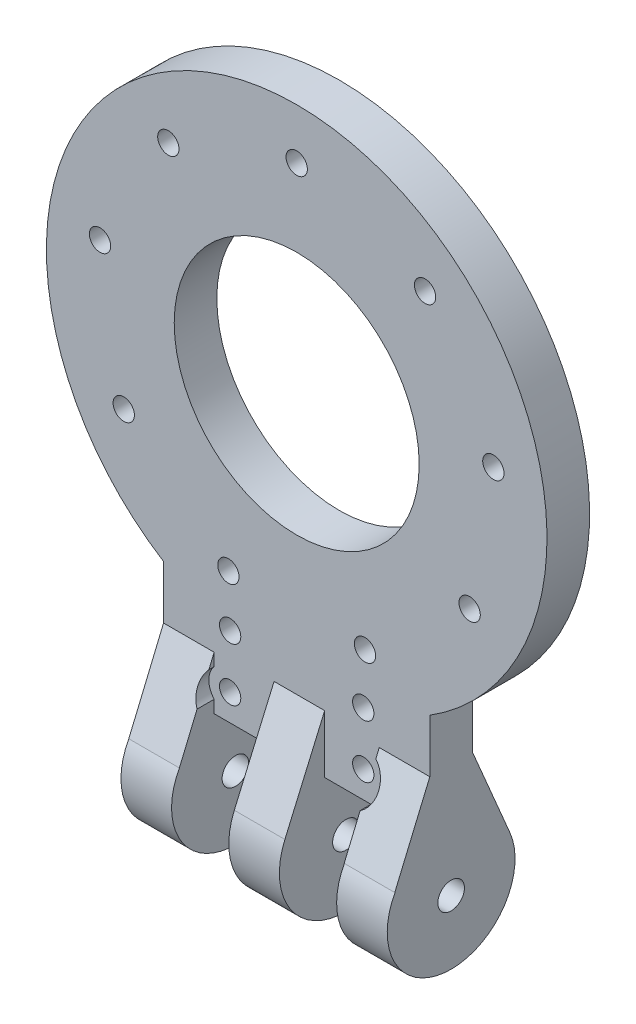
SolidWorks part; units mm, degrees
ref_plane "前视基准面" through (0, 0, 0) normal (0, 0, 1) x (1, 0, 0)
ref_plane "上视基准面" through (0, 0, 0) normal (0, 1, 0) x (1, 0, 0)
ref_plane "右视基准面" through (0, 0, 0) normal (1, 0, 0) x (0, 0, -1)
sketch "草图1" plane through (0, 0, 0) normal (0, 0, 1) x (1, 0, 0)
  line L0 (32.476, 31.0495) -> (36.9303, 56.3113) construction
  line L1 (-25, -10) -> (25, -10)
  line L2 (-25, -10) -> (-25, 10)
  line L3 (-25, 10) -> (25, 10) construction
  line L4 (25, -10) -> (25, 10)
  line L5 (-25, -10) -> (25, 10) construction
  line L6 (-25, 10) -> (25, -10) construction
  line L7 (0, 87.2995) -> (-24.1045, 78.5262) construction
  line L8 (-24.1045, 78.5262) -> (-36.9303, 56.3113) construction
  line L9 (-36.9303, 56.3113) -> (-32.476, 31.0495) construction
  line L10 (-32.476, 31.0495) -> (-12.8258, 14.561) construction
  line L11 (-12.8258, 14.561) -> (12.8258, 14.561) construction
  line L12 (12.8258, 14.561) -> (32.476, 31.0495) construction
  line L13 (36.9303, 56.3113) -> (24.1045, 78.5262) construction
  line L14 (24.1045, 78.5262) -> (0, 87.2995) construction
  line L15 (0, 10) -> (0, -10) construction
  arc A0 (25, 10) -> (-25, 10) centre (0, 49.7995) ccw
  circle A1 centre (0, 49.7995) radius 37.5 construction
  circle A3 centre (24.1045, 78.5262) radius 2
  circle A4 centre (36.9303, 56.3113) radius 2
  circle A5 centre (32.476, 31.0495) radius 2
  circle A6 centre (12.8258, 14.561) radius 2
  circle A7 centre (-12.8258, 14.561) radius 2
  circle A8 centre (-32.476, 31.0495) radius 2
  circle A9 centre (-36.9303, 56.3113) radius 2
  circle A10 centre (-24.1045, 78.5262) radius 2
  circle A11 centre (0, 87.2995) radius 2
  circle A12 centre (12.5, -5) radius 2
  circle A13 centre (-12.5, -5) radius 2
  circle A14 centre (12.5, 5) radius 2
  circle A15 centre (-12.5, 5) radius 2
  circle A16 centre (0, 49.7995) radius 23
  point P0 (0, 0)
  point P36 (0, 49.7995)
  dimension "D3" = 47
  dimension "D4" = 9
  dimension "D5" = 4
  dimension "D6" = 75
  dimension "D7" = 25.2618
  dimension "D8" = 4
  dimension "D11" = 5
  dimension "D12" = 10
  dimension "D13" = 46
  dimension "D1" = 50
  dimension "D2" = 20
  dimension "D9" = 12.5
  dimension "D10" = 2
extrude "凸台-拉伸1" add sketch "草图1" along normal blind 8
sketch "草图2" plane through (-25, 0, 0) normal (-1, 0, 0) x (0, 0, 1)
  arc A0 (0, -10) -> (8, -10) centre (4, -21.3137) ccw
  circle A1 centre (4, -21.3137) radius 2.5
  line M2 (0, -10) -> (8, -10)
  dimension "D1" = 12
  dimension "D2" = 5
extrude "凸台-拉伸2" add sketch "草图2" against normal blind 9.5 contours A0 A1 M2
sketch "草图4" plane through (25, 0, 0) normal (1, 0, 0) x (0, 0, -1)
  line L4 (0, -10) -> (0, 10)
  line L5 (0, 10) -> (-8, 10)
  line L6 (-8, 10) -> (-8, -10)
  line L7 (-8, -10) -> (0, -10)
  line L11 (-8, -10) -> (0, -10)
  arc A0 (-8, -10) -> (0, -10) centre (-4, -21.3137) ccw
  circle A1 centre (-4, -21.3137) radius 2.5
  dimension "D1" = 0
extrude "凸台-拉伸4" add sketch "草图4" against normal blind 9.5
sketch "草图5" plane through (0, -10, 0) normal (0, -1, 0) x (1, 0, 0)
  line L0 (-15.5, 8) -> (15.5, 8) construction
  line L1 (0, 8) -> (0, 0) construction
ref_plane "基准面5" through (0.5, 0, 0) normal (-1, 0, 0) x (0, 0, 1)
sketch "草图6" plane through (0.5, 0, 0) normal (-1, 0, 0) x (0, 0, 1)
  arc A0 (0, -10) -> (8, -10) centre (4, -21.3137) ccw
  circle A1 centre (4, -21.3137) radius 2.5
  dimension "D1" = 12
  dimension "D2" = 5
extrude "拉伸-薄壁1" add sketch "草图6" along normal mid plane 9.5 thin contours A1
sketch "草图7" plane through (-25, 0, 0) normal (-1, 0, 0) x (0, 0, 1)
  line L0 (8, 0) -> (15.4824, -17.8274)
  line L1 (8, 10) -> (8, -10) construction
  arc A0 (0, -10) -> (8, -10) centre (4, -21.3137) ccw construction
rib "筋1" sketch "草图7" sketch "草图7" thickness 9.5 extrusion direction parallel to sketch draft on no parameters "D1"=9.5
sketch "草图10" plane through (-25, 0, 0) normal (-1, 0, 0) x (0, 0, 1)
  line L0 (0, 0) -> (-7.0486, -16.631) construction
  line L1 (0, 10) -> (0, -10) construction
  line L2 (8, 0) -> (0, 0) construction
  arc A0 (0, -10) -> (8, -10) centre (4, -21.3137) ccw construction
sketch "草图12" plane through (25, 0, 0) normal (1, 0, 0) x (0, 0, -1)
  line L0 (-8, 0) -> (-14.5853, -15.5378)
  line L2 (-8, 0) -> (-3.3764, -1.9426)
  line L3 (-3.3764, -1.9426) -> (-9.6471, -16.8675)
  line L4 (-9.6471, -16.8675) -> (-14.5853, -15.5378)
  arc A1 (-8, -10) -> (0, -10) centre (-4, -21.3137) ccw construction
extrude "凸台-拉伸5" add sketch "草图12" against normal up to surface (9.5 mm away) up to face at (15.5, -21.3137, 1.5)
sketch "草图14" plane through (25, 0, 0) normal (1, 0, 0) x (0, 0, -1)
  line L0 (0, 0) -> (7.0486, -16.631)
  line L1 (0, -10) -> (0, 10) construction
  arc A0 (-14.5271, -15.5534) -> (0, -10) centre (-4, -21.3137) ccw construction
sketch "草图15" plane through (-25, 0, 0) normal (-1, 0, 0) x (0, 0, 1)
  line L1 (0, 0) -> (-7.0486, -16.631)
  line L2 (-7.0486, -16.631) -> (-1.0813, -18.152)
  line L3 (-1.0813, -18.152) -> (5.6051, -2.3756)
  line L4 (5.6051, -2.3756) -> (0, 0)
  arc A0 (0, -10) -> (8, -10) centre (4, -21.3137) ccw construction
extrude "凸台-拉伸6" add sketch "草图15" against normal up to surface (9.5 mm away) up to face at (-15.5, -21.3137, 6.5)
sketch "草图20" plane through (0, 0, 8) normal (0, 0, 1) x (1, 0, 0)
  line L0 (0.5, 30.6594) -> (0.5, -30.6594) construction
  circle A0 centre (-12.5, -5) radius 4
  circle A1 centre (13.5, -5) radius 4
extrude "切除-拉伸3" cut sketch "草图20" along normal up to surface (2.1191 mm away)
sketch "草图23" plane through (0.5, 0, 0) normal (-1, 0, 0) x (0, 0, 1)
  line L0 (0, 0) -> (-7.3682, -16.1162)
  line L1 (-7.3682, -16.1162) -> (-3.8416, -16.9118)
  line L2 (-3.8416, -16.9118) -> (3.2466, -1.408)
  line L3 (3.2466, -1.408) -> (-0.1261, -0.2759)
  arc A0 (0, -9.471) -> (8, -9.471) centre (4, -21.3137) ccw construction
extrude "凸台-拉伸7" add sketch "草图23" along normal up to surface and the other way up to surface contours L2 L3 L0 L1 up to face at (-4.25, -15.8212, 4) other way up to face at (5.25, -15.8212, 4)
sketch "草图25" plane through (0, 0, 8) normal (0, 0, 1) x (1, 0, 0)
  line L0 (-15.5, 0) -> (15.5, 0) construction
sketch "草图26" plane through (0.5, 0, 0) normal (-1, 0, 0) x (0, 0, 1)
  line L0 (8, 0.8797) -> (15.468, -16.3402)
  line L1 (8, 0) -> (8, -2.3542) construction
  arc A0 (-7.3682, -16.1162) -> (8, -9.471) centre (4, -21.3137) ccw construction
  point P2 (0, 0)
rib "筋2" sketch "草图14" sketch "草图14" thickness 9.5 extrusion direction parallel to sketch draft on no parameters "D1"=9.5
rib "筋3" sketch "草图26" sketch "草图26" thickness 9.5 extrusion direction parallel to sketch draft on no parameters "D1"=9.5
